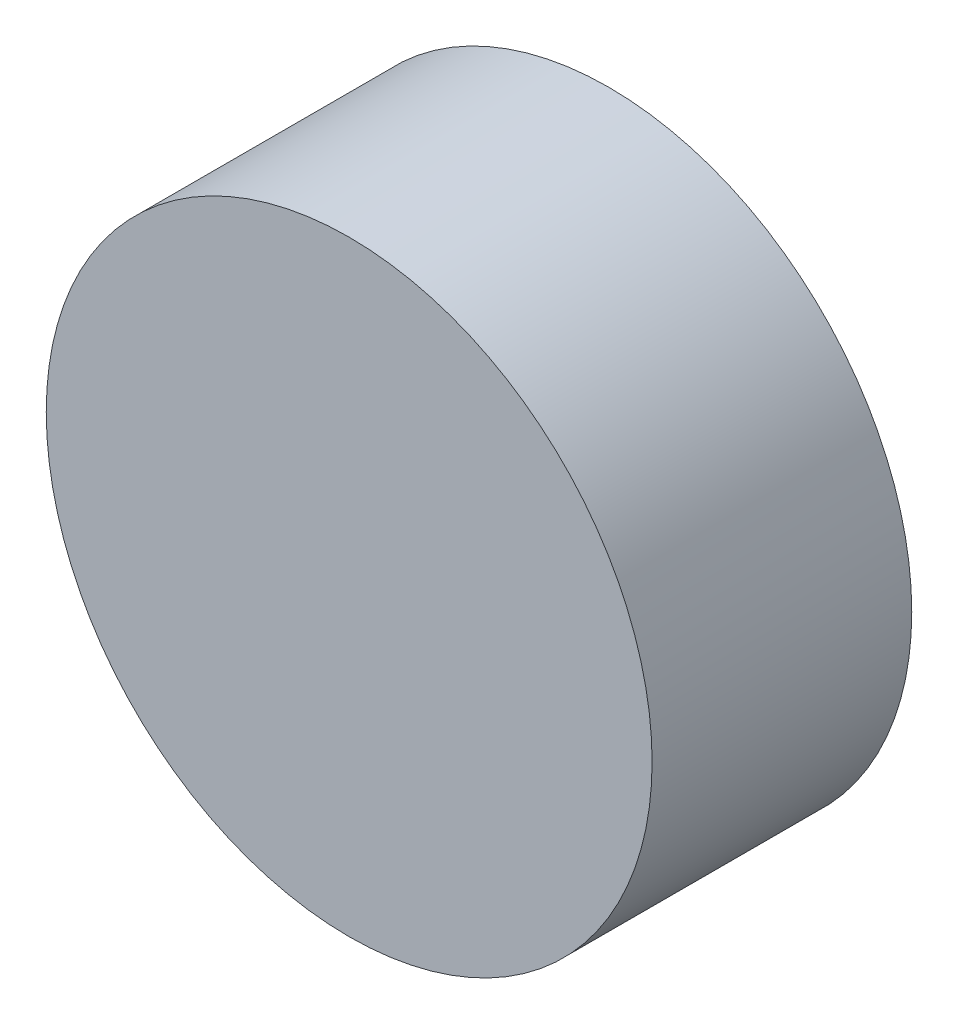
SolidWorks part; units mm, degrees
ref_plane "前基準面" through (0, 0, 0) normal (0, 0, 1) x (1, 0, 0)
ref_plane "上基準面" through (0, 0, 0) normal (0, 1, 0) x (1, 0, 0)
ref_plane "右基準面" through (0, 0, 0) normal (1, 0, 0) x (0, 0, -1)
sketch "草圖1" plane through (0, 0, 0) normal (0, 0, 1) x (1, 0, 0)
  circle A0 centre (0, 0) radius 31.5
  dimension "D1" = 63
extrude "填料-伸長1" add sketch "草圖1" along normal blind 27
